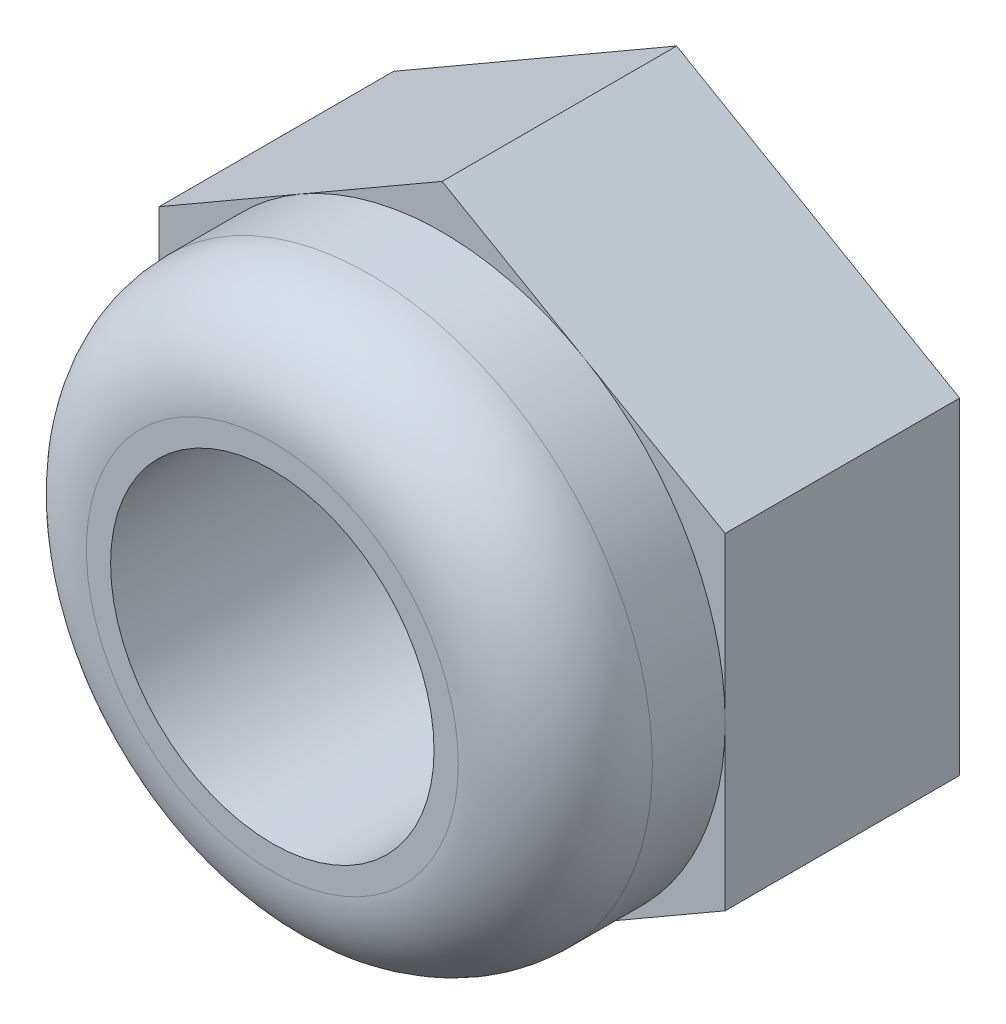
SolidWorks part; units mm, degrees
material "AISI 304"
ref_plane "Front Plane" through (0, 0, 0) normal (0, 0, 1) x (1, 0, 0)
ref_plane "Top Plane" through (0, 0, 0) normal (0, 1, 0) x (1, 0, 0)
ref_plane "Right Plane" through (0, 0, 0) normal (1, 0, 0) x (0, 0, -1)
sketch "草图1" plane through (0, 0, 0) normal (0, 0, 1) x (1, 0, 0)
  line L1 (3.5, -2.0207) -> (3.5, 2.0207)
  line L2 (3.5, 2.0207) -> (0, 4.0415)
  line L3 (0, 4.0415) -> (-3.5, 2.0207)
  line L4 (-3.5, 2.0207) -> (-3.5, -2.0207)
  line L5 (-3.5, -2.0207) -> (0, -4.0415)
  line L6 (0, -4.0415) -> (3.5, -2.0207)
  circle A0 centre (0, 0) radius 3.5 construction
  dimension "D1" = 7
extrude "凸台-拉伸1" add sketch "草图1" along normal blind 2.9
sketch "草图2" plane through (0, 0, 2.9) normal (0, 0, 1) x (1, 0, 0)
  line L0 (3.5, 2.0207) -> (0, 4.0415) construction
  circle A0 centre (0, 0) radius 3.5
extrude "凸台-拉伸2" add sketch "草图2" along normal blind 2.1
sketch "草图3" plane through (0, 0, 5) normal (0, 0, 1) x (1, 0, 0)
  circle A0 centre (0, 0) radius 2
  dimension "D1" = 4
extrude "切除-拉伸1" cut sketch "草图3" against normal through all
fillet "圆角1" radius 1.2 1 edges at (3.5, 0, 5)
